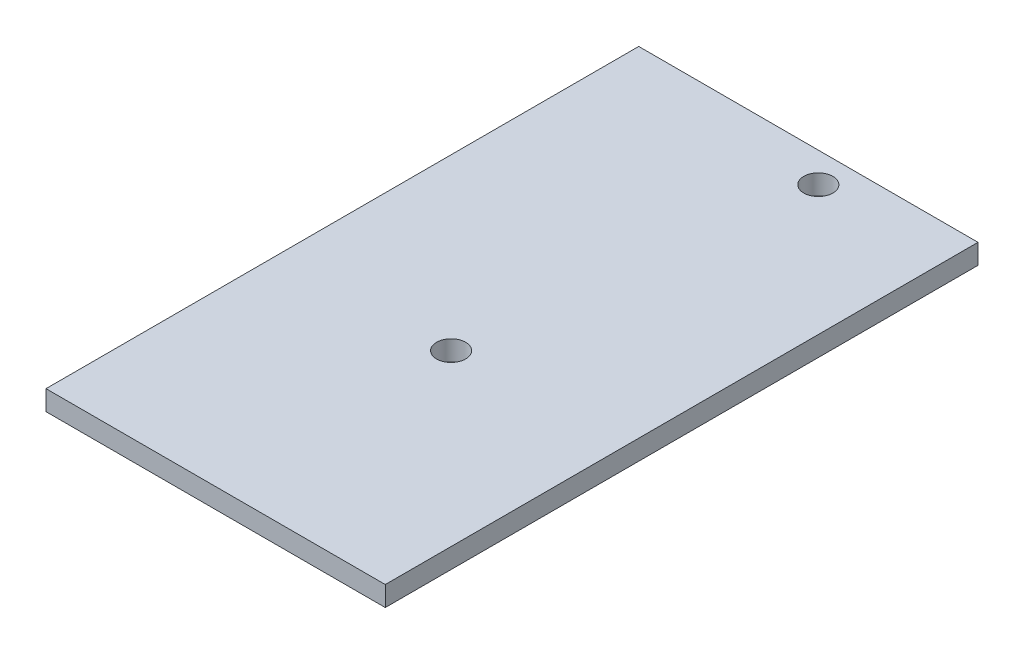
SolidWorks part; units mm, degrees
ref_plane "Front Plane" through (0, 0, 0) normal (0, 0, 1) x (1, 0, 0)
ref_plane "Top Plane" through (0, 0, 0) normal (0, 1, 0) x (1, 0, 0)
ref_plane "Right Plane" through (0, 0, 0) normal (1, 0, 0) x (0, 0, -1)
sketch "Sketch1" plane through (0, 0, 0) normal (0, 1, 0) x (1, 0, 0)
  line L1 (-26.67, 43.18) -> (16.51, 43.18)
  line L2 (-26.67, 43.18) -> (-26.67, -32.258)
  line L3 (-26.67, -32.258) -> (16.51, -32.258)
  line L4 (16.51, 43.18) -> (16.51, -32.258)
  dimension "D1" = 26.67
  dimension "D2" = 43.18
  dimension "D3" = 43.18
  dimension "D4" = 75.438
extrude "Boss-Extrude1" add sketch "Sketch1" along normal blind 2.54
sketch "Sketch2" plane through (0, 2.54, 0) normal (0, 1, 0) x (1, 0, 0)
  line L1 (16.51, -32.258) -> (16.51, 43.18) construction
  line L2 (16.51, 43.18) -> (-26.67, 43.18) construction
  circle A0 centre (-5.08, -2.286) radius 3.9064
  circle A1 centre (0, 39.37) radius 2.1168
  dimension "D1" = 21.59
  dimension "D2" = 3.81
  dimension "D3" = 16.51
  dimension "D4" = 41.656
hole_wizard "M3 Clearance Hole1" positions "Sketch3" profile "Sketch4" hole size "M3" standard "ANSI Metric"
sketch "Sketch3" plane through (0, 2.54, 0) normal (0, 1, 0) x (1, 0, 0)
  point P3 (0, 39.37)
  point P8 (-5.08, -2.286)
sketch "Sketch4" plane through (0, 2.54, -39.37) normal (1, 0, 0) x (0, 0, 1)
  line L0 (0, 0) -> (0, 26.5116)
  line L1 (0, 26.5116) -> (1.85, 25.4)
  line L2 (1.85, 25.4) -> (1.85, 0)
  line L5 (1.85, 0) -> (0, 0)
  line L10 (0, 26.5116) -> (-1.85, 25.4) construction
  line L11 (0, -6.35) -> (0, 107.95) construction
  dimension "Hole Dia." = 3.7
  dimension "Hole Depth" = 25.4
  dimension "Drill Angle" = 118
